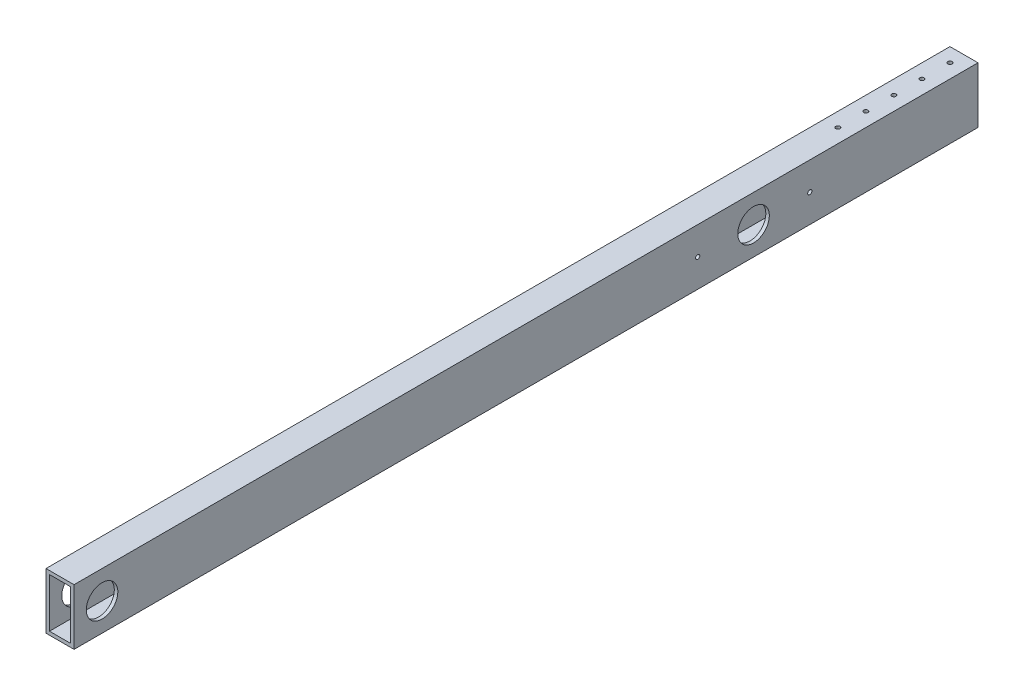
SolidWorks part; units mm, degrees
material "6061-T6 (SS)"
ref_plane "Front Plane" through (0, 0, 0) normal (0, 0, 1) x (1, 0, 0)
ref_plane "Top Plane" through (0, 0, 0) normal (0, 1, 0) x (1, 0, 0)
ref_plane "Right Plane" through (0, 0, 0) normal (1, 0, 0) x (0, 0, -1)
sketch "Sketch1" plane through (0, 0, 0) normal (0, 0, 1) x (1, 0, 0)
  line L0 (-9.525, 22.225) -> (9.525, 22.225)
  line L1 (-12.7, 25.4) -> (12.7, 25.4)
  line L2 (-12.7, 25.4) -> (-12.7, -25.4)
  line L3 (-12.7, -25.4) -> (12.7, -25.4)
  line L4 (12.7, 25.4) -> (12.7, -25.4)
  line L5 (-12.7, 25.4) -> (12.7, -25.4) construction
  line L6 (-12.7, -25.4) -> (12.7, 25.4) construction
  line L7 (9.525, 22.225) -> (9.525, -22.225)
  line L8 (-9.525, -22.225) -> (9.525, -22.225)
  line L9 (-9.525, 22.225) -> (-9.525, -22.225)
  point P0 (0, 0)
  dimension "D1" = 50.8
  dimension "D2" = 25.4
  dimension "D3" = 3.175
extrude "Boss-Extrude1" add sketch "Sketch1" along normal mid plane 819.15
sketch "Sketch7" plane through (0, 25.4, 0) normal (0, 1, 0) x (1, 0, 0)
  line L0 (-12.7, -409.575) -> (-12.7, 409.575) construction
  line L1 (12.7, 409.575) -> (-12.7, 409.575) construction
  circle A0 centre (0, 396.875) radius 1.905
  circle A1 centre (0, 371.475) radius 1.905
  circle A2 centre (0, 346.075) radius 1.905
  circle A3 centre (0, 320.675) radius 1.905
  circle A4 centre (0, 295.275) radius 1.905
  dimension "D1" = 3.81
  dimension "D2" = 12.7
  dimension "D3" = 12.7
  dimension "D4" = 5
extrude "Cut-Extrude1" cut sketch "Sketch7" against normal through all
sketch "Sketch8" plane through (12.7, 0, 0) normal (1, 0, 0) x (0, 0, -1)
  line L0 (409.575, -25.4) -> (409.575, 25.4) construction
  line L1 (-409.575, 25.4) -> (409.575, 25.4) construction
  line L2 (-409.575, -25.4) -> (-409.575, 25.4) construction
  circle A0 centre (155.575, 0) radius 1.905
  circle A1 centre (257.175, 0) radius 1.905
  circle A2 centre (206.1843, 0) radius 14.2875
  circle A3 centre (-384.175, 0) radius 14.2875
  dimension "D1" = 3.81
  dimension "D4" = 28.575
  dimension "D6" = 25.4
  dimension "D3" = 254
  dimension "D5" = 25.4
  dimension "D7" = 25.4
  dimension "D2" = 2
extrude "Cut-Extrude2" cut sketch "Sketch8" against normal through all
